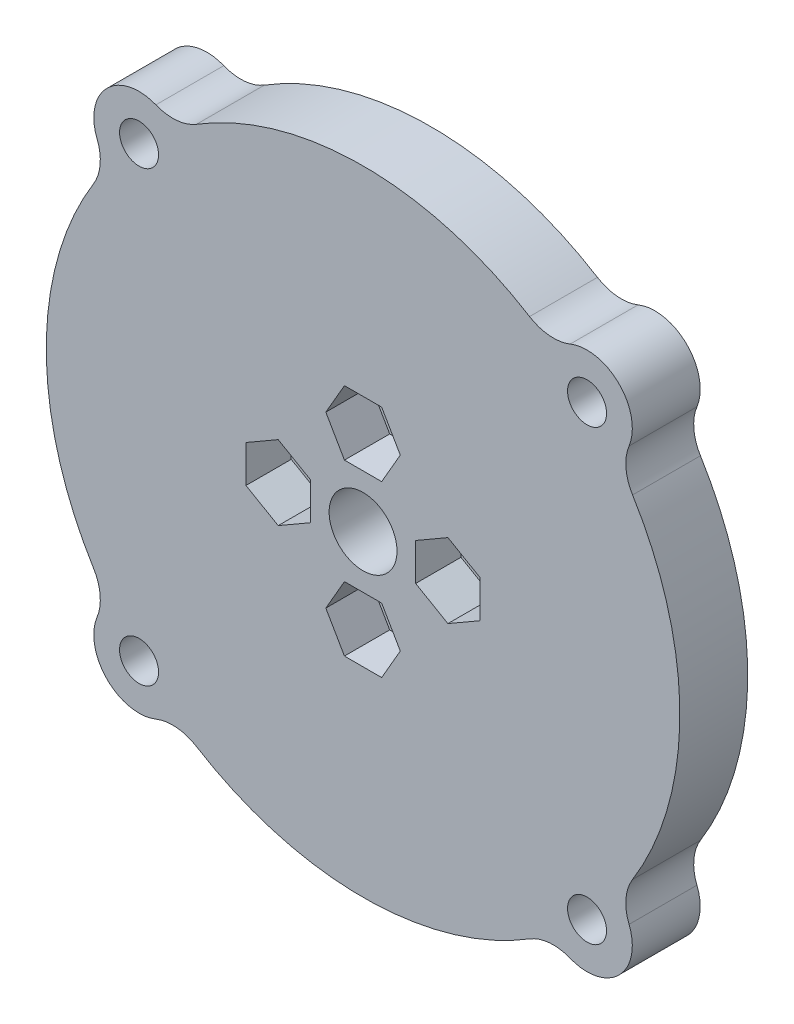
SolidWorks part; units mm, degrees
material "ABS"
ref_plane "Front Plane" through (0, 0, 0) normal (0, 0, 1) x (1, 0, 0)
ref_plane "Top Plane" through (0, 0, 0) normal (0, 1, 0) x (1, 0, 0)
ref_plane "Right Plane" through (0, 0, 0) normal (1, 0, 0) x (0, 0, -1)
sketch "Sketch1" plane through (0, 0, 0) normal (0, 0, 1) x (1, 0, 0)
  line L0 (-19.799, 19.799) -> (19.799, -19.799) construction
  line L1 (-19.799, -19.799) -> (19.799, 19.799) construction
  line L2 (-28, 0) -> (28, 0) construction
  arc A0 (22.4182, -16.7758) -> (22.4182, 16.7758) centre (0, 0) ccw
  circle A1 centre (-19.799, 19.799) radius 1.725
  circle A2 centre (19.799, 19.799) radius 1.725
  circle A3 centre (-19.799, -19.799) radius 1.725
  circle A4 centre (19.799, -19.799) radius 1.725
  arc A5 (22.4182, 16.7758) -> (16.7758, 22.4182) centre (19.799, 19.799) ccw
  arc A6 (-16.7758, 22.4182) -> (-22.4182, 16.7758) centre (-19.799, 19.799) ccw
  arc A7 (-22.4182, -16.7758) -> (-16.7758, -22.4182) centre (-19.799, -19.799) ccw
  arc A8 (16.7758, -22.4182) -> (22.4182, -16.7758) centre (19.799, -19.799) ccw
  arc A9 (-16.7758, -22.4182) -> (16.7758, -22.4182) centre (0, 0) ccw
  arc A10 (-22.4182, 16.7758) -> (-22.4182, -16.7758) centre (0, 0) ccw
  arc A11 (16.7758, 22.4182) -> (-16.7758, 22.4182) centre (0, 0) ccw
  circle A12 centre (0, 0) radius 7.5 construction
  circle A20 centre (0, 0) radius 3
  circle A21 centre (0, 7.5) radius 1.725
  circle A22 centre (-7.5, 0) radius 1.725
  circle A23 centre (0, -7.5) radius 1.725
  circle A24 centre (7.5, 0) radius 1.725
  dimension "D1" = 15
  dimension "D2" = 6
  dimension "D3" = 3.45
  dimension "D4" = 56
  dimension "D5" = 45
  dimension "D6" = 8
other "AlignGroup1"
other "AlignGroup2"
other "AlignGroup3"
other "AlignGroup4"
other "AlignGroup5"
other "AlignGroup6"
other "AlignGroup7"
other "AlignGroup8"
other "AlignGroup9"
other "AlignGroup10"
other "AlignGroup11"
other "AlignGroup12"
other "AlignGroup13"
other "AlignGroup14"
extrude "Boss-Extrude3" add sketch "Sketch1" along normal blind 6
sketch "Sketch2" plane through (0, 0, 6) normal (0, 0, 1) x (1, 0, 0)
  line L1 (3.2909, 7.5) -> (1.6454, 10.35)
  line L2 (1.6454, 10.35) -> (-1.6454, 10.35)
  line L3 (-1.6454, 10.35) -> (-3.2909, 7.5)
  line L4 (-3.2909, 7.5) -> (-1.6454, 4.65)
  line L5 (-1.6454, 4.65) -> (1.6454, 4.65)
  line L6 (1.6454, 4.65) -> (3.2909, 7.5)
  line L7 (-4.65, 1.6454) -> (-7.5, 3.2909)
  line L8 (-7.5, 3.2909) -> (-10.35, 1.6454)
  line L9 (-10.35, 1.6454) -> (-10.35, -1.6454)
  line L10 (-10.35, -1.6454) -> (-7.5, -3.2909)
  line L11 (-7.5, -3.2909) -> (-4.65, -1.6454)
  line L12 (-4.65, -1.6454) -> (-4.65, 1.6454)
  line L13 (10.35, -1.6454) -> (10.35, 1.6454)
  line L14 (10.35, 1.6454) -> (7.5, 3.2909)
  line L15 (7.5, 3.2909) -> (4.65, 1.6454)
  line L16 (4.65, 1.6454) -> (4.65, -1.6454)
  line L17 (4.65, -1.6454) -> (7.5, -3.2909)
  line L18 (7.5, -3.2909) -> (10.35, -1.6454)
  line L19 (3.2909, -7.5) -> (1.6454, -4.65)
  line L20 (1.6454, -4.65) -> (-1.6454, -4.65)
  line L21 (-1.6454, -4.65) -> (-3.2909, -7.5)
  line L22 (-3.2909, -7.5) -> (-1.6454, -10.35)
  line L23 (-1.6454, -10.35) -> (1.6454, -10.35)
  line L24 (1.6454, -10.35) -> (3.2909, -7.5)
  circle A0 centre (0, 7.5) radius 2.85 construction
  circle A1 centre (-7.5, 0) radius 2.85 construction
  circle A2 centre (7.5, 0) radius 2.85 construction
  circle A3 centre (0, -7.5) radius 2.85 construction
  dimension "D1" = 5.7
other "AlignGroup15"
other "AlignGroup16"
extrude "Cut-Extrude1" cut sketch "Sketch2" against normal blind 4
fillet "Fillet1" radius 4 8 edges at (22.4182, -16.7758, 3) (16.7758, -22.4182, 3) (-16.7758, -22.4182, 3) (-22.4182, -16.7758, 3) (-22.4182, 16.7758, 3) (-16.7758, 22.4182, 3) (16.7758, 22.4182, 3) (22.4182, 16.7758, 3)
equation "\"D3@Sketch1\"=3.00mm+\"print_free@Parameters@FabricationParameters.sldprt\""
equation "\"D1@Sketch2\"=5.50mm+\"print_fit@Parameters@FabricationParameters.sldprt\""
